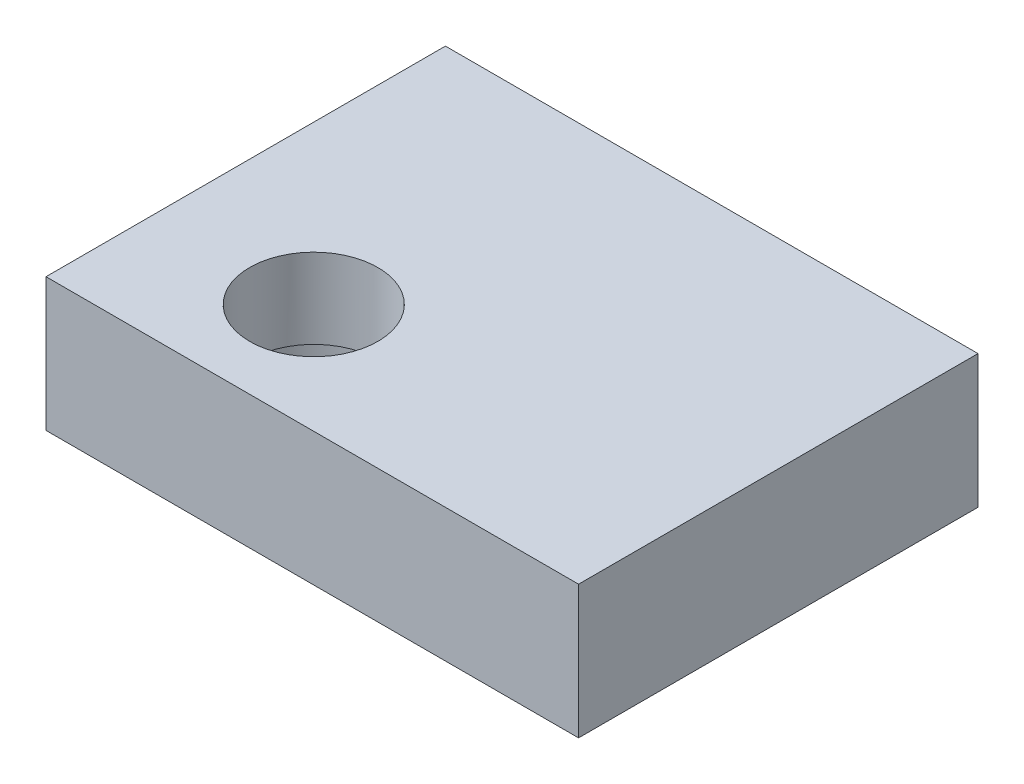
SolidWorks part; units mm, degrees
ref_plane "Front Plane" through (0, 0, 0) normal (0, 0, 1) x (1, 0, 0)
ref_plane "Top Plane" through (0, 0, 0) normal (0, 1, 0) x (1, 0, 0)
ref_plane "Right Plane" through (0, 0, 0) normal (1, 0, 0) x (0, 0, -1)
sketch "Sketch1" plane through (0, 0, 0) normal (0, 1, 0) x (1, 0, 0)
  line L1 (-20, -15) -> (20, -15)
  line L2 (-20, -15) -> (-20, 15)
  line L3 (-20, 15) -> (20, 15)
  line L4 (20, -15) -> (20, 15)
  line L5 (-20, -15) -> (20, 15) construction
  line L6 (-20, 15) -> (20, -15) construction
  point P0 (0, 0)
  dimension "D1" = 40
  dimension "D2" = 30
extrude "Boss-Extrude1" add sketch "Sketch1" along normal blind 10
sketch "Sketch2" plane through (0, 0, 0) normal (0, -1, 0) x (-1, 0, 0)
  line L0 (20, 15) -> (-20, -15) construction
  line L1 (20, -15) -> (-20, 15) construction
  line L2 (20, -15) -> (-20, -15) construction
  line L3 (20, 0) -> (-20, 0) construction
  line L4 (20, 15) -> (20, -15) construction
  line L5 (-20, -15) -> (-20, 15) construction
  line L6 (0, -15) -> (0, 15) construction
  line L7 (-20, 15) -> (20, 15) construction
  circle A0 centre (-13.3333, -10) radius 1.55
  circle A1 centre (-13.3333, 10) radius 1.55
  circle A2 centre (13.3333, 10) radius 1.55
  circle A3 centre (8.14, -6.75) radius 6.3
  dimension "D1" = 3.1
  dimension "D5" = 12.6
  dimension "D2" = 5
  dimension "D3" = 11.86
  dimension "D4" = 8.25
extrude "Cut-Extrude1" cut sketch "Sketch2" against normal blind 4
sketch "Sketch3" plane through (0, 10, 0) normal (0, 1, 0) x (1, 0, 0)
  line L6 (-20, 15) -> (-20, -15) construction
  line L10 (-20, -15) -> (20, -15) construction
  circle A0 centre (-8.14, -6.75) radius 4.8125
  dimension "D1" = 9.625
  dimension "D2" = 11.86
  dimension "D3" = 8.25
extrude "Cut-Extrude2" cut sketch "Sketch3" against normal up to surface (10 mm away) up to face at (-8.14, 0, 0.45)
